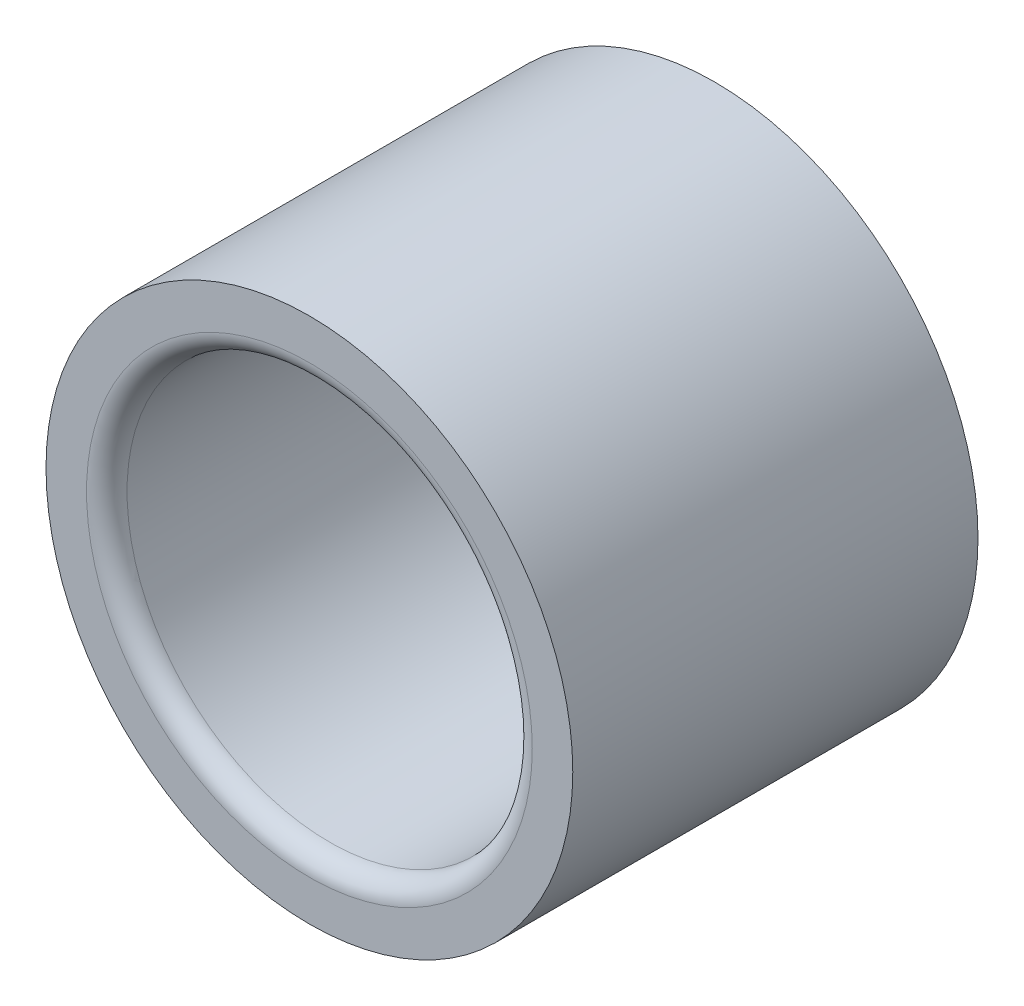
SolidWorks part; units mm, degrees
ref_plane "Front Plane" through (0, 0, 0) normal (0, 0, 1) x (1, 0, 0)
ref_plane "Top Plane" through (0, 0, 0) normal (0, 1, 0) x (1, 0, 0)
ref_plane "Right Plane" through (0, 0, 0) normal (1, 0, 0) x (0, 0, -1)
sketch "Sketch1" plane through (0, 0, 0) normal (0, 0, 1) x (1, 0, 0)
  circle A0 centre (0, 0) radius 13
  dimension "D1" = 26
extrude "Boss-Extrude1" add sketch "Sketch1" along normal blind 20
sketch "Sketch2" plane through (0, 0, 20) normal (0, 0, 1) x (1, 0, 0)
  circle A0 centre (0, 0) radius 10
  dimension "D1" = 20
extrude "Cut-Extrude1" cut sketch "Sketch2" against normal blind 17
fillet "Fillet3" radius 1 1 edges at (10, 0, 20)
